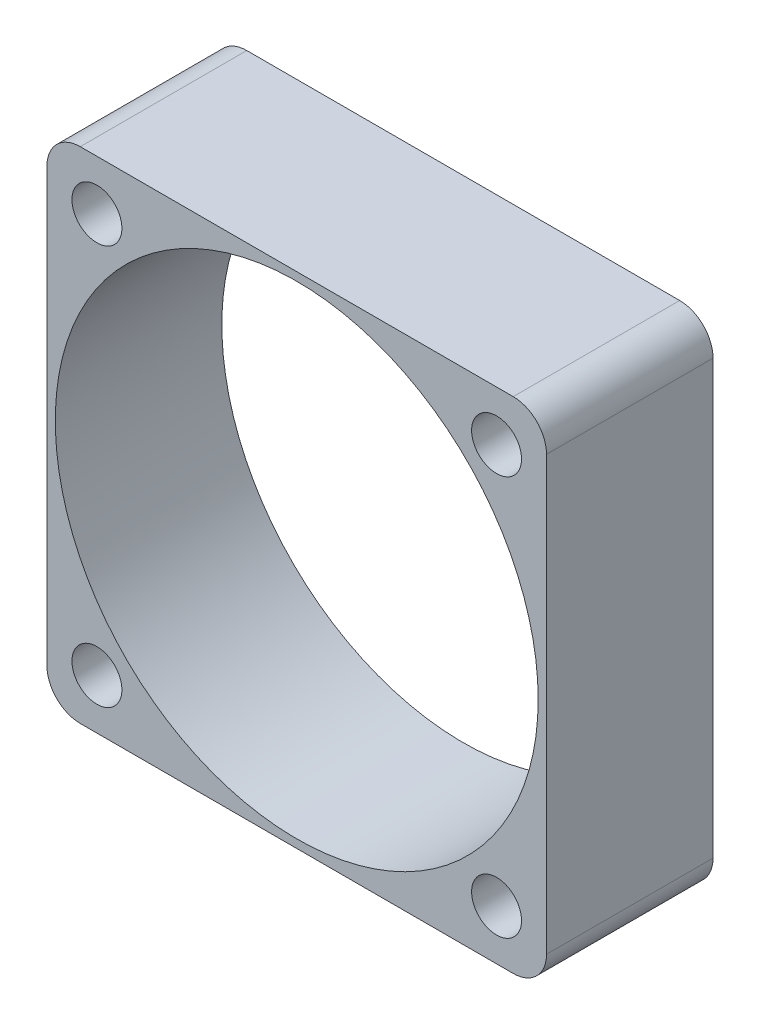
SolidWorks part; units mm, degrees
ref_plane "前基準面" through (0, 0, 0) normal (0, 0, 1) x (1, 0, 0)
ref_plane "上基準面" through (0, 0, 0) normal (0, 1, 0) x (1, 0, 0)
ref_plane "右基準面" through (0, 0, 0) normal (1, 0, 0) x (0, 0, -1)
sketch "草圖1" plane through (0, 0, 0) normal (0, 0, 1) x (1, 0, 0)
  line L1 (-15, 15) -> (15, 15)
  line L2 (-15, 15) -> (-15, -15)
  line L3 (-15, -15) -> (15, -15)
  line L4 (15, 15) -> (15, -15)
  circle A0 centre (0, 0) radius 14.5
  point P4 (0, 15)
  point P6 (-15, 0)
  dimension "D3" = 29
  dimension "D1" = 30
  dimension "D2" = 30
extrude "填料-伸長1" add sketch "草圖1" along normal blind 10
fillet "圓角1" radius 2 4 edges at (-15, -15, 5) (15, -15, 5) (15, 15, 5) (-15, 15, 5)
sketch "草圖2" plane through (0, 0, 10) normal (0, 0, 1) x (1, 0, 0)
  line L0 (-15, 0) -> (15, 0) construction
  line L1 (-15, 13) -> (-15, -13) construction
  line L2 (15, -13) -> (15, 13) construction
  line L3 (0, 15) -> (0, -15) construction
  line L4 (13, 15) -> (-13, 15) construction
  line L5 (-13, -15) -> (13, -15) construction
  circle A0 centre (-12, 12) radius 1.5
  circle A1 centre (12, 12) radius 1.5
  circle A2 centre (12, -12) radius 1.5
  circle A3 centre (-12, -12) radius 1.5
  point P22 (-11.2256, 15.2564)
  dimension "D1" = 3
  dimension "D2" = 12
  dimension "D3" = 12
  dimension "D4" = 3
extrude "除料-伸長1" cut sketch "草圖2" against normal blind 10
